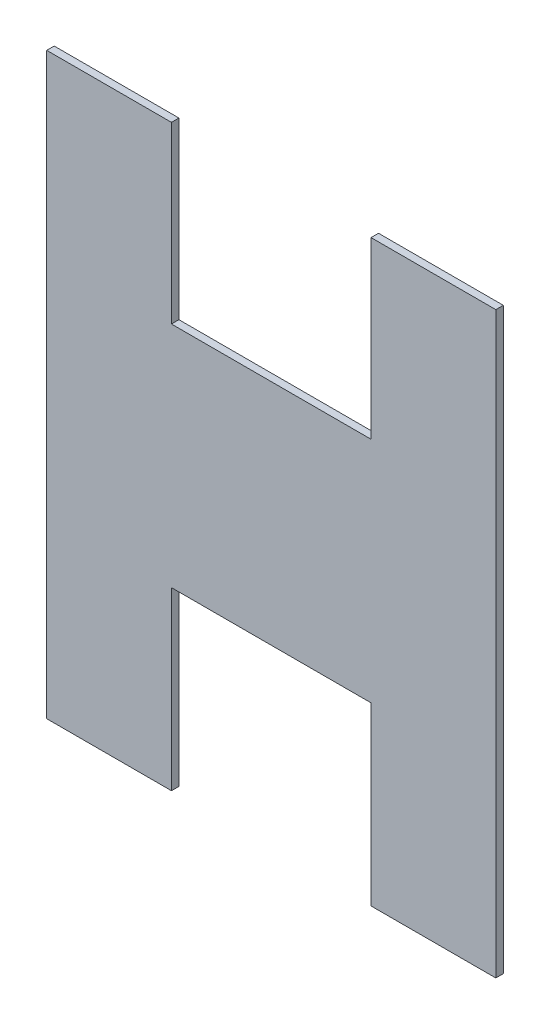
SolidWorks part; units mm, degrees
ref_plane "Plan de face" through (0, 0, 0) normal (0, 0, 1) x (1, 0, 0)
ref_plane "Plan de dessus" through (0, 0, 0) normal (0, 1, 0) x (1, 0, 0)
ref_plane "Plan de droite" through (0, 0, 0) normal (1, 0, 0) x (0, 0, -1)
sketch "Esquisse1" plane through (0, 0, 0) normal (0, 0, 1) x (1, 0, 0)
  line L0 (-40, 83.2564) -> (-40, 13.2564)
  line L1 (90, -148.7436) -> (40, -148.7436)
  line L7 (-40, 13.2564) -> (40, 13.2564)
  line L8 (40, 13.2564) -> (40, 83.2564)
  line L10 (-40, -148.7436) -> (-40, -78.2436)
  line L11 (-40, -78.2436) -> (40, -78.2436)
  line L12 (40, -78.2436) -> (40, -148.7436)
  line L13 (-40, -148.7436) -> (-90, -148.7436)
  line L16 (-90, -148.7436) -> (-90, 83.2564)
  line L18 (-95, -148.7436) -> (-40, -148.7436) construction
  line L21 (-90, 83.2564) -> (-40, 83.2564)
  line L25 (40, 13.2564) -> (-40, 13.2564) construction
  line L28 (90, 83.2564) -> (90, -148.7436)
  line L29 (40, 83.2564) -> (90, 83.2564)
  line L30 (-40, 86.2564) -> (-135, 86.2564) construction
  point P0 (0, 0)
  point P8 (0, 13.2564)
  dimension "D2" = 3
  dimension "D3" = 50
  dimension "D4" = 80
  dimension "D5" = 80
  dimension "D6" = 0
  dimension "D7" = 0
  dimension "D10" = 50
extrude "Boss.-Extru.1" add sketch "Esquisse1" along normal blind 3
